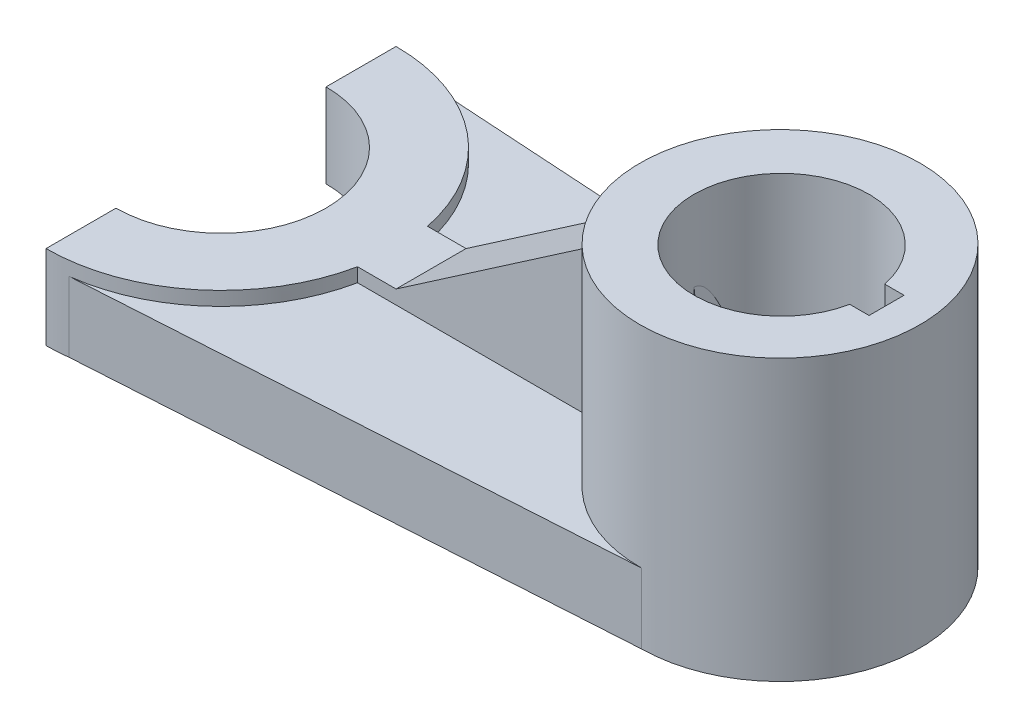
SolidWorks part; units mm, degrees
material "Cast Carbon Steel"
ref_plane "Front Plane" through (0, 0, 0) normal (0, 0, 1) x (1, 0, 0)
ref_plane "Top Plane" through (0, 0, 0) normal (0, 1, 0) x (1, 0, 0)
ref_plane "Right Plane" through (0, 0, 0) normal (1, 0, 0) x (0, 0, -1)
sketch "Sketch1" plane through (0, 0, 0) normal (0, 1, 0) x (1, 0, 0)
  line L0 (0, 45.6388) -> (0, -44.0671) construction
  line L1 (-67.3958, 0) -> (40, 0) construction
  line L2 (-40, -25) -> (-40, -15)
  line L4 (-40, 25) -> (40.0608, 20)
  line L5 (-40, -25) -> (40.0608, -20)
  line L6 (40.0608, 20) -> (40.0608, -20)
  line L11 (-40, 15) -> (-40, 25)
  line L12 (55, 0) -> (95.594, 0) construction
  arc A0 (-40, -24.9922) -> (-40, 24.9922) centre (-40.6229, 0) ccw
  arc A1 (-40, -15) -> (-40, 15) centre (-40, 0) ccw
  point P10 (40, 0)
  point P11 (-40, 0)
  point P16 (0, 0)
  point P19 (0, 0)
  point P21 (40.0608, -20.1744)
  dimension "D2" = 50
  dimension "D3" = 40
sketch "Sketch5" plane through (0, 0, 0) normal (0, 1, 0) x (1, 0, 0)
sketch "Sketch6" plane through (0, 0, 0) normal (0, 1, 0) x (1, 0, 0)
sketch "Sketch7" plane through (0, 0, 0) normal (0, 1, 0) x (1, 0, 0)
extrude "Boss-Extrude2" add sketch "Sketch1" along normal blind 10.0139 contours L4 L6 L5 L2 A1 L11
sketch "Sketch16" plane through (0, 0, 0) normal (0, 1, 0) x (1, 0, 0)
  line L0 (-40.5063, 0) -> (42.0956, 0) construction
sketch "Sketch17" plane through (0, 0, 0) normal (0, 1, 0) x (1, 0, 0)
  line L0 (-40, 25) -> (-40, 15)
  line L1 (-40, -15) -> (-40, -25)
  arc A0 (-40, -25) -> (-40, 25) centre (-40, 0) ccw
  arc A1 (-40, -15) -> (-40, 15) centre (-40, 0) ccw
extrude "Boss-Extrude3" add sketch "Sketch17" along normal blind 12
sketch "Sketch18" plane through (0, 0, 0) normal (0, 1, 0) x (1, 0, 0)
  line L0 (-40.5063, 0) -> (42.0956, 0) construction
  line L1 (40.0608, 20) -> (40.0608, 19.9988)
  circle A0 centre (39.8424, 0) radius 20
  circle A1 centre (39.8424, 0) radius 12.5
sketch "Sketch19" plane through (0, 0, 0) normal (0, 1, 0) x (1, 0, 0)
extrude "Boss-Extrude6" add sketch "Sketch18" along normal blind 40 contours A0
sketch "Sketch26" plane through (0, 0, 0) normal (0, 1, 0) x (1, 0, 0)
  line L0 (40.0608, 20) -> (40.0608, -20)
  line L1 (-36.8895, 24.8057) -> (40.0608, 20) construction
  circle A0 centre (40.0608, 0) radius 12.5
  circle A1 centre (40.0608, 0) radius 20
extrude "Cut-Extrude2" cut sketch "Sketch26" along normal blind 40 contours A0
sketch "Sketch27" plane through (0, 0, 0) normal (0, 1, 0) x (1, 0, 0)
  line L0 (40.0608, 20) -> (40.0608, -19.9988)
  line L1 (40.0608, 0.0006) -> (52.4897, 0.0006)
  line L2 (55.0608, 0.0006) -> (55.0608, 2.4996)
  line L3 (55.0608, 0.0006) -> (55.0608, -2.4994)
  line L4 (55.0608, 2.4996) -> (52.2359, 2.4996)
  line L5 (55.0608, -2.4994) -> (52.2357, -2.4994)
  arc A0 (40.0608, -19.9988) -> (40.0608, 19.9988) centre (39.8424, 0) ccw construction
  circle A1 centre (40.0608, 0.0006) radius 12.4289
sketch "Sketch28" plane through (0, 0, 0) normal (0, 1, 0) x (1, 0, 0)
sketch "Sketch29" plane through (0, 0, 0) normal (0, 1, 0) x (1, 0, 0)
sketch "Sketch33" plane through (0, 0, 0) normal (0, 1, 0) x (1, 0, 0)
extrude "Cut-Extrude5" cut sketch "Sketch27" along normal blind 40 contours A1 L5 L3 L2 L4
sketch "Sketch35" plane through (0, 0, 0) normal (0, 0, 1) x (1, 0, 0)
  line L0 (-15, 12) -> (-10, 12)
  line L2 (-15, 10.0139) -> (19.8424, 10.0139)
  line L3 (19.8424, 40) -> (19.8424, 10.0139) construction
  line L4 (-36.8895, 10.0139) -> (40.0608, 10.0139) construction
  line L6 (-10, 12) -> (19.8424, 32.5)
  line L7 (-15, 12) -> (-18.0738, 12)
  line L8 (-15, 12) -> (-40, 12) construction
  line L9 (-15, 10.0139) -> (-18.5579, 10.0139)
  line L11 (19.8424, 10.0139) -> (25.4503, 10.0139)
  line L12 (-18.0738, 12) -> (-18.5579, 10.0139)
  line L13 (26.3633, 32.5) -> (25.4503, 10.0139)
  line L14 (19.8424, 32.5) -> (25.0156, 36.0537)
  line L16 (26.3633, 32.5) -> (25.0156, 36.0537)
sketch "Sketch36" plane through (0, 0, 0) normal (0, 0, 1) x (1, 0, 0)
  line L0 (19.8424, 32.5) -> (23.6922, 32.5)
  line L1 (19.8424, 10.0139) -> (23.6922, 10.0139)
  point P6 (0, 0)
sketch "Sketch37" plane through (0, 0, 0) normal (0, 0, 1) x (1, 0, 0)
sketch "Sketch38" plane through (0, 0, 0) normal (0, 0, 1) x (1, 0, 0)
  line L0 (-15, 12) -> (-18.2491, 12)
  line L1 (-15, 12) -> (-40, 12) construction
  line L2 (-15, 10.0139) -> (-19.3092, 10.0139)
  line L3 (-36.8895, 10.0139) -> (40.0608, 10.0139) construction
extrude "Boss-Extrude8" add sketch "Sketch35" along normal blind 5 contours L6 L14 L16 L13 L11 L2 L9 L12 L7 L0
ref_plane "Plane2" through (-10, 12, 0) normal (0.8243, 0.5662, 0) x (0, 0, -1)
ref_plane "Plane3" through (-10, 12, 0) normal (0.8243, 0.5662, 0) x (0, 0, -1)
sketch "Sketch41" plane through (0, 0, 0) normal (0, 0, 1) x (1, 0, 0)
  line L0 (19.8424, 32.5) -> (-10, 12)
  line L1 (-10, 12) -> (-16.6246, 12)
  line L2 (-15, 12) -> (-18.2491, 12) construction
  line L3 (-16.6246, 12) -> (-16.6246, 10.0139)
  line L4 (-15, 10.0139) -> (-19.3092, 10.0139) construction
  line L5 (-16.6246, 10.0139) -> (29.7899, 10.0139)
  line L6 (29.7899, 10.0139) -> (27.4778, 29.1762)
  line L7 (19.8424, 32.5) -> (25.5975, 36.4534)
  line L8 (25.5975, 36.4534) -> (27.4778, 29.1762)
extrude "Boss-Extrude9" add sketch "Sketch41" against normal blind 5 contours L8 L6 L5 L3 L1 L0 L7
